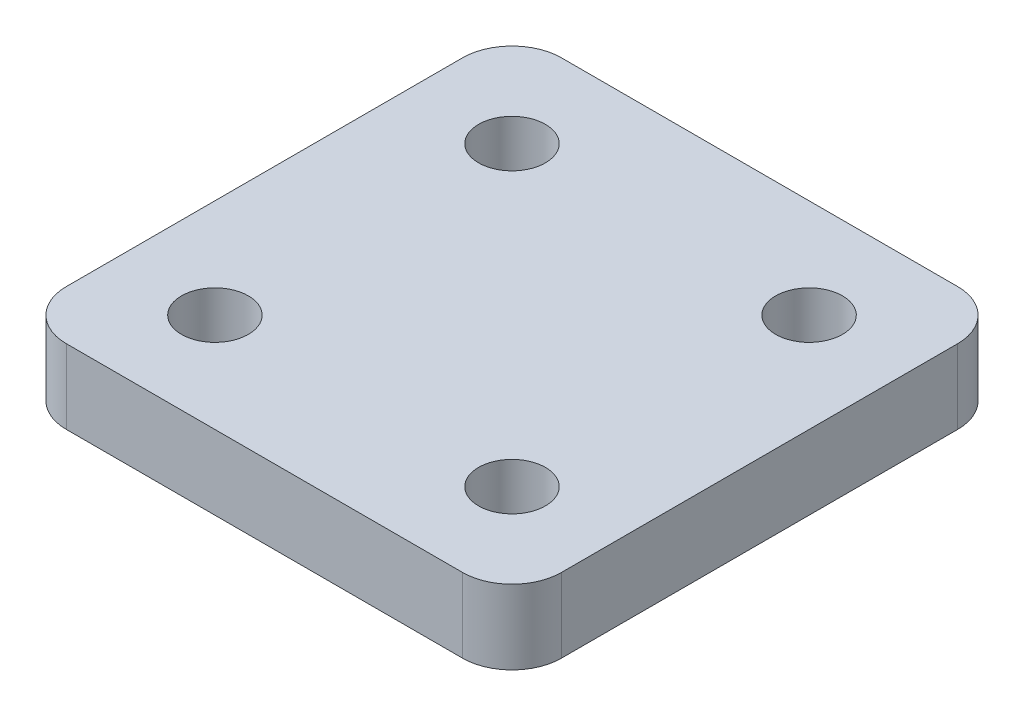
SolidWorks part; units mm, degrees
material "碳纤维"
ref_plane "前视基准面" through (0, 0, 0) normal (0, 0, 1) x (1, 0, 0)
ref_plane "上视基准面" through (0, 0, 0) normal (0, 1, 0) x (1, 0, 0)
ref_plane "右视基准面" through (0, 0, 0) normal (1, 0, 0) x (0, 0, -1)
sketch "草图1" plane through (0, 0, 0) normal (0, 1, 0) x (1, 0, 0)
  line L1 (-10, -10) -> (10, -10)
  line L2 (-10, -10) -> (-10, 10)
  line L3 (-10, 10) -> (10, 10)
  line L4 (10, -10) -> (10, 10)
  line L5 (0, 10) -> (0, -10) construction
  line L6 (-10, 0) -> (10, 0) construction
  circle A0 centre (-6, 6) radius 1.35
  circle A1 centre (6, 6) radius 1.35
  circle A2 centre (6, -6) radius 1.35
  circle A3 centre (-6, -6) radius 1.35
  point P0 (0, 0)
  dimension "D4" = 2.7
  dimension "D1" = 12
  dimension "D2" = 12
  dimension "D3" = 20
  dimension "D5" = 10
  dimension "D6" = 10
extrude "凸台-拉伸1" add sketch "草图1" along normal blind 3
fillet "圆角1" radius 2 4 edges at (-10, 1.5, 10) (-10, 1.5, -10) (10, 1.5, -10) (10, 1.5, 10)
